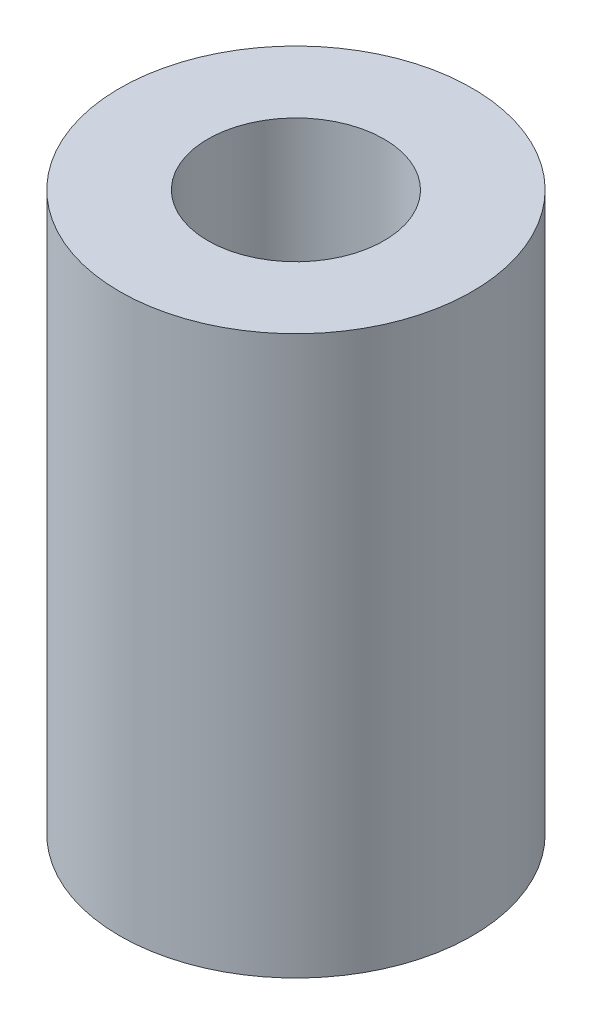
SolidWorks part; units mm, degrees
ref_plane "Front Plane" through (0, 0, 0) normal (0, 0, 1) x (1, 0, 0)
ref_plane "Top Plane" through (0, 0, 0) normal (0, 1, 0) x (1, 0, 0)
ref_plane "Right Plane" through (0, 0, 0) normal (1, 0, 0) x (0, 0, -1)
sketch "Sketch1" plane through (0, 0, 0) normal (0, 1, 0) x (1, 0, 0)
  circle A0 centre (0, 0) radius 3
  circle A1 centre (0, 0) radius 6
extrude "Boss-Extrude1" add sketch "Sketch1" along normal blind 19
